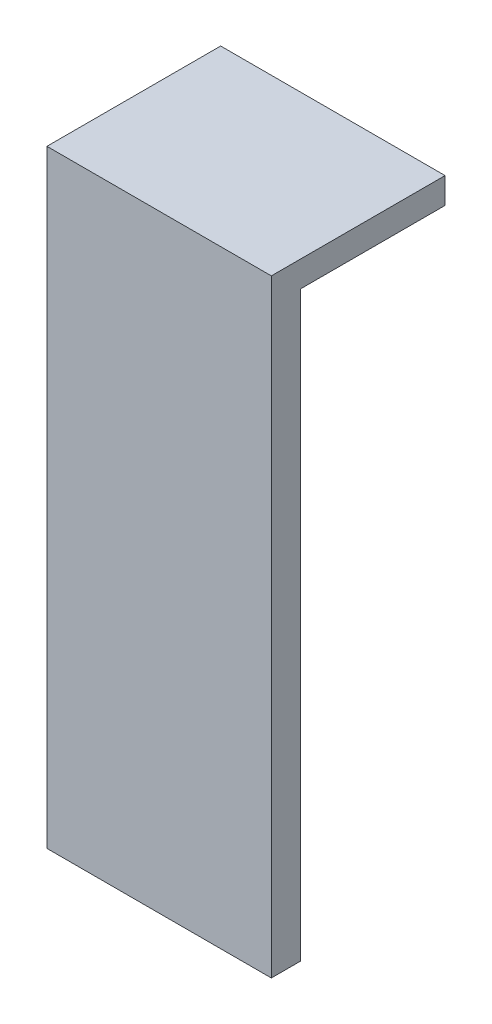
SolidWorks part; units mm, degrees
ref_plane "Front Plane" through (0, 0, 0) normal (0, 0, 1) x (1, 0, 0)
ref_plane "Top Plane" through (0, 0, 0) normal (0, 1, 0) x (1, 0, 0)
ref_plane "Right Plane" through (0, 0, 0) normal (1, 0, 0) x (0, 0, -1)
sketch "Sketch1" plane through (0, 0, 0) normal (0, 1, 0) x (1, 0, 0)
  line L1 (-4.2545, 1.016) -> (3.6195, 1.016)
  line L2 (-4.2545, 1.016) -> (-4.2545, 0)
  line L3 (-4.2545, 0) -> (3.6195, 0)
  line L4 (3.6195, 1.016) -> (3.6195, 0)
  point P4 (3.6195, 0.508)
  dimension "D1" = 7.874
  dimension "D2" = 1.016
extrude "Boss-Extrude1" add sketch "Sketch1" along normal blind 21.336
sketch "Sketch2" plane through (0, 0, -1.016) normal (0, 0, -1) x (-1, 0, 0)
  line L0 (-3.6195, 21.336) -> (-3.6195, 0) construction
  line L1 (-3.6195, 21.336) -> (4.2545, 21.336)
  line L2 (-3.6195, 21.336) -> (-3.6195, 20.4278)
  line L3 (-3.6195, 20.4278) -> (4.2545, 20.4278)
  line L4 (4.2545, 21.336) -> (4.2545, 20.4278)
  line L5 (4.2545, 21.336) -> (4.2545, 0) construction
extrude "Boss-Extrude2" add sketch "Sketch2" along normal blind 5.08
